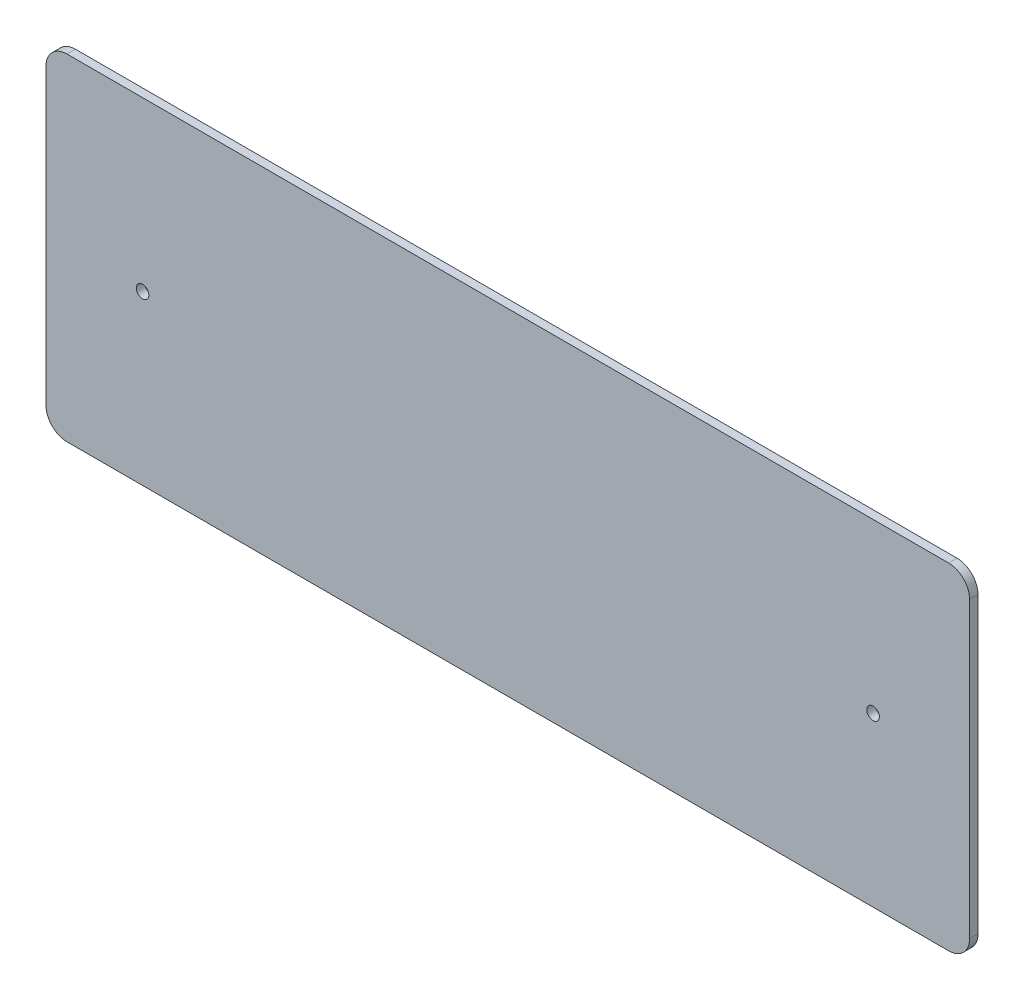
SolidWorks part; units mm, degrees
material "S30403 GB/T3280-2015"
ref_plane "Front" through (0, 0, 0) normal (0, 0, 1) x (1, 0, 0)
ref_plane "Top" through (0, 0, 0) normal (0, 1, 0) x (1, 0, 0)
ref_plane "Right" through (0, 0, 0) normal (1, 0, 0) x (0, 0, -1)
sketch "草图1" plane through (0, 0, 0) normal (0, 0, 1) x (1, 0, 0)
  line L0 (0, 40) -> (0, -40) construction
  line L1 (-110, 40) -> (110, 40)
  line L2 (-110, 40) -> (-110, -40)
  line L3 (-110, -40) -> (110, -40)
  line L4 (110, 40) -> (110, -40)
  line L5 (-110, 0) -> (110, 0) construction
  circle A0 centre (-87, 0) radius 1.5
  circle A1 centre (87, 0) radius 1.5
  point P12 (0, 0)
  dimension "D3" = 3
  dimension "D4" = 174
  dimension "D1" = 220
  dimension "D2" = 80
extrude "凸台-拉伸1" add sketch "草图1" along normal blind 2 contours L4 L1 L2 L3 A1 A0
fillet "圆角1" radius 5 4 edges at (110, -40, 1) (110, 40, 1) (-110, -40, 1) (-110, 40, 1)
